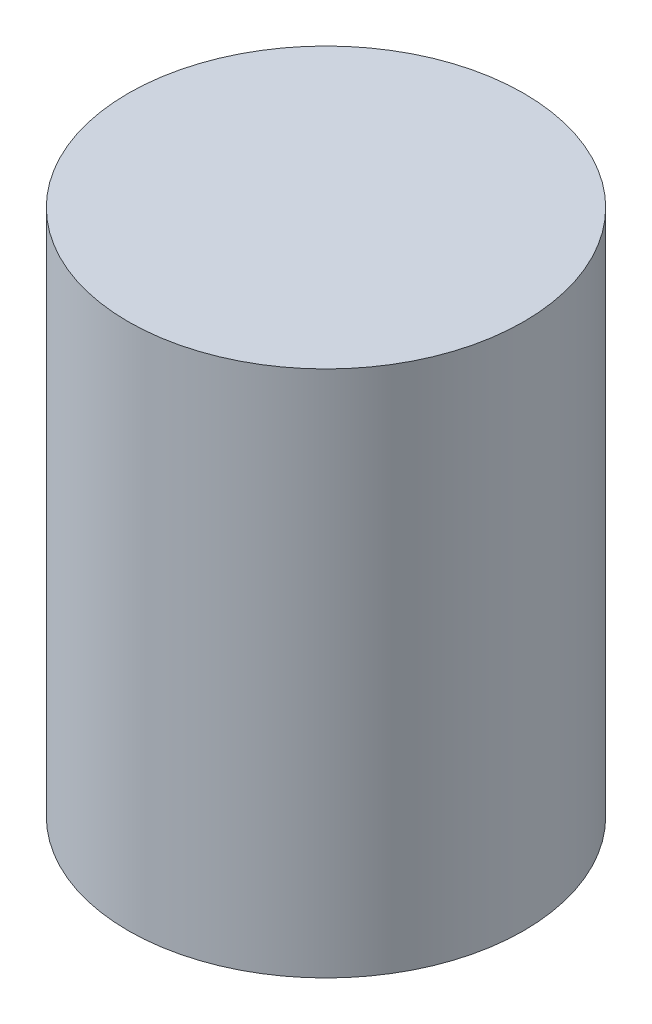
SolidWorks part; units mm, degrees
ref_plane "前视基准面" through (0, 0, 0) normal (0, 0, 1) x (1, 0, 0)
ref_plane "上视基准面" through (0, 0, 0) normal (0, 1, 0) x (1, 0, 0)
ref_plane "右视基准面" through (0, 0, 0) normal (1, 0, 0) x (0, 0, -1)
sketch "草图1" plane through (0, 0, 0) normal (0, 1, 0) x (1, 0, 0)
  circle A0 centre (0, 0) radius 15
extrude "凸台-拉伸1" add sketch "草图1" along normal blind 40
